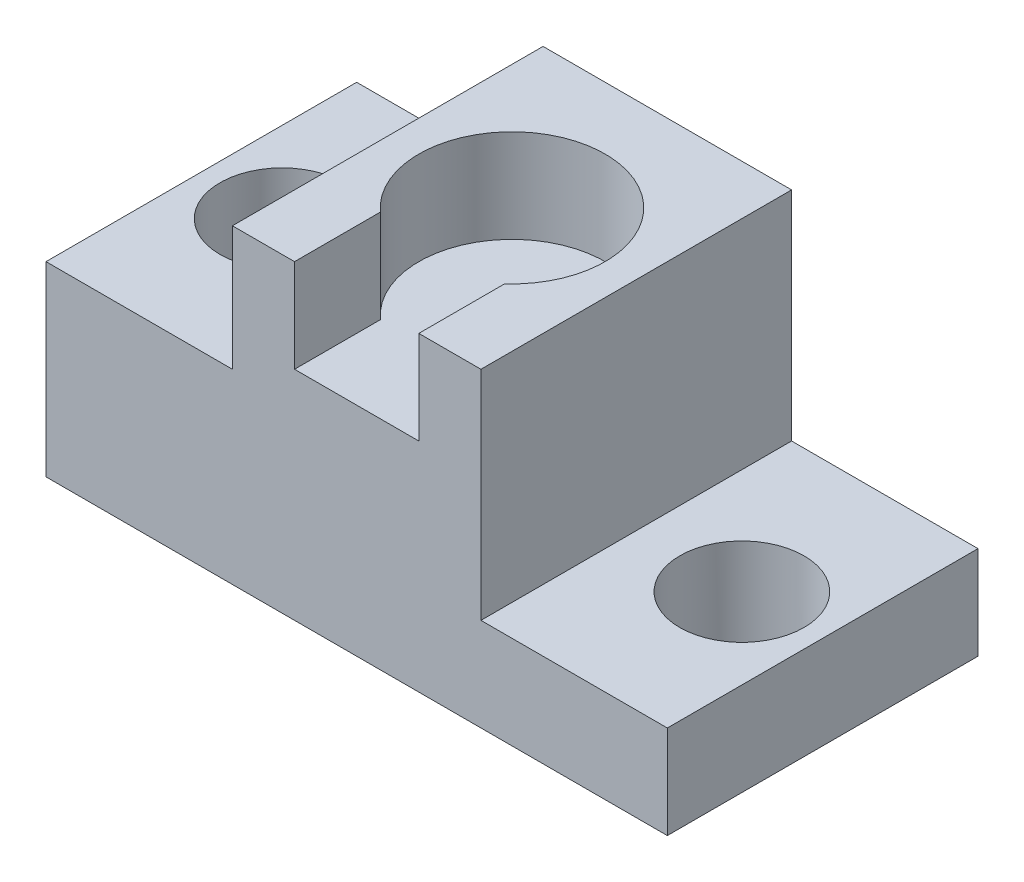
SolidWorks part; units mm, degrees
ref_plane "Plano frontal" through (0, 0, 0) normal (0, 0, 1) x (1, 0, 0)
ref_plane "Plano superior" through (0, 0, 0) normal (0, 1, 0) x (1, 0, 0)
ref_plane "Plano direito" through (0, 0, 0) normal (1, 0, 0) x (0, 0, -1)
sketch "Esboço1" plane through (0, 0, 0) normal (0, 0, 1) x (1, 0, 0)
  line L0 (-50, 0) -> (50, 0)
  line L1 (-50, 0) -> (-50, 30)
  line L2 (-50, 30) -> (-20, 30)
  line L3 (-20, 30) -> (-20, 50)
  line L4 (-20, 50) -> (20, 50)
  line L5 (20, 50) -> (20, 15)
  line L6 (20, 15) -> (50, 15)
  line L7 (50, 15) -> (50, 0)
  dimension "D1" = 30
  dimension "D2" = 15
  dimension "D3" = 50
  dimension "D4" = 30
  dimension "D5" = 40
  dimension "D6" = 100
extrude "Ressalto-extrusão1" add sketch "Esboço1" along normal blind 50
sketch "Esboço2" plane through (0, 50, 0) normal (0, 1, 0) x (1, 0, 0)
  line L0 (-10, -25) -> (10, -25) construction
  line L1 (-50, -50) -> (-50, 0) construction
  line L3 (0, -7.4317) -> (0, -43.9738) construction
  line L7 (-10, -36.1803) -> (-10, -50)
  line L8 (20, -50) -> (-20, -50) construction
  line L9 (10, -36.1803) -> (10, -50)
  line L11 (20, 0) -> (-20, 0) construction
  circle A0 centre (-37, -25) radius 10
  circle A1 centre (37, -25) radius 10.0004
  circle A2 centre (0, -25) radius 15
  dimension "D2" = 20
  dimension "D3" = 20.0009
  dimension "D5" = 30
  dimension "D8" = 25
  dimension "D1" = 13
  dimension "D4" = 13
  dimension "D6" = 25
  dimension "D7" = 25
  dimension "D9" = 10
extrude "Corte-extrusão1" cut sketch "Esboço2" against normal through all contours A0 | A1
sketch "Esboço3" plane through (0, 50, 0) normal (0, 1, 0) x (1, 0, 0)
  line L0 (-10, -25) -> (10, -25) construction
  line L3 (-10, -36.1803) -> (-10, -50)
  line L5 (20, -50) -> (-20, -50) construction
  line L6 (10, -36.1803) -> (10, -50)
  line L7 (10, -50) -> (-10, -50)
  line L8 (-20, 0) -> (-50, 0) construction
  circle A0 centre (0, -25) radius 15
  arc A1 (-10, -36.1803) -> (9.9353, -36.2378) centre (0, -25) ccw
  dimension "D1" = 30
  dimension "D4" = 20
  dimension "D2" = 10
  dimension "D3" = 25
extrude "Corte-extrusão2" cut sketch "Esboço3" against normal blind 15 contours A0
sketch "Esboço5" plane through (0, 50, 0) normal (0, 1, 0) x (1, 0, 0)
  line L0 (-10, -25) -> (10, -25) construction
  line L1 (0, 0) -> (0, -50) construction
  line L2 (20, -50) -> (-20, -50) construction
  line L3 (-10, -36.1803) -> (-10, -50)
  line L4 (-10, -50) -> (10, -50)
  line L5 (10, -50) -> (10, -36.1803)
  circle A0 centre (0, -25) radius 15 construction
  arc A1 (10, -36.1803) -> (-10, -36.1803) centre (0, -25) cw
  point P7 (0, -25)
  dimension "D1" = 10
extrude "Corte-extrusão3" cut sketch "Esboço5" against normal blind 15
